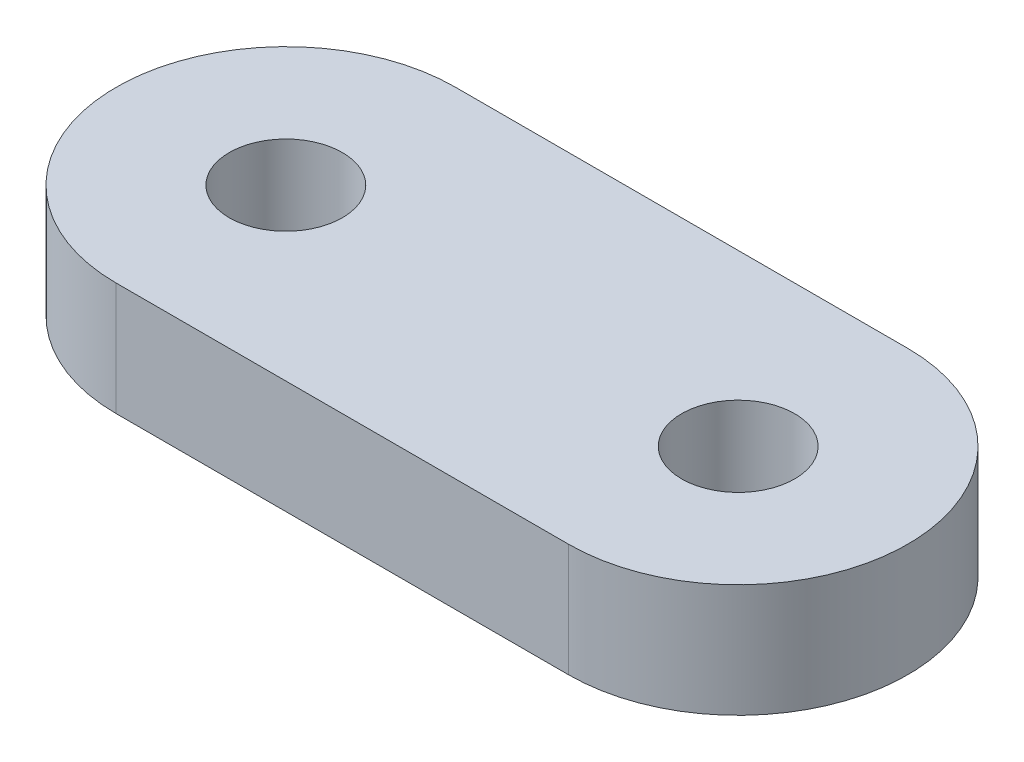
SolidWorks part; units mm, degrees
ref_plane "前视基准面" through (0, 0, 0) normal (0, 0, 1) x (1, 0, 0)
ref_plane "上视基准面" through (0, 0, 0) normal (0, 1, 0) x (1, 0, 0)
ref_plane "右视基准面" through (0, 0, 0) normal (1, 0, 0) x (0, 0, -1)
sketch "草图1" plane through (0, 0, 0) normal (0, 1, 0) x (1, 0, 0)
  line L0 (0, 0) -> (-4, 0) construction
  line L1 (0, -1.5) -> (-4, -1.5)
  line L2 (0, 1.5) -> (-4, 1.5)
  arc A0 (0, -1.5) -> (0, 1.5) centre (0, 0) ccw
  arc A1 (-4, 1.5) -> (-4, -1.5) centre (-4, 0) ccw
  circle A2 centre (-4, 0) radius 0.5
  circle A3 centre (0, 0) radius 0.5
  point P3 (-2, 0)
  dimension "D1" = 1.5
  dimension "D2" = 1
  dimension "D3" = 1
  dimension "D4" = 4
extrude "凸台-拉伸1" add sketch "草图1" along normal blind 1
